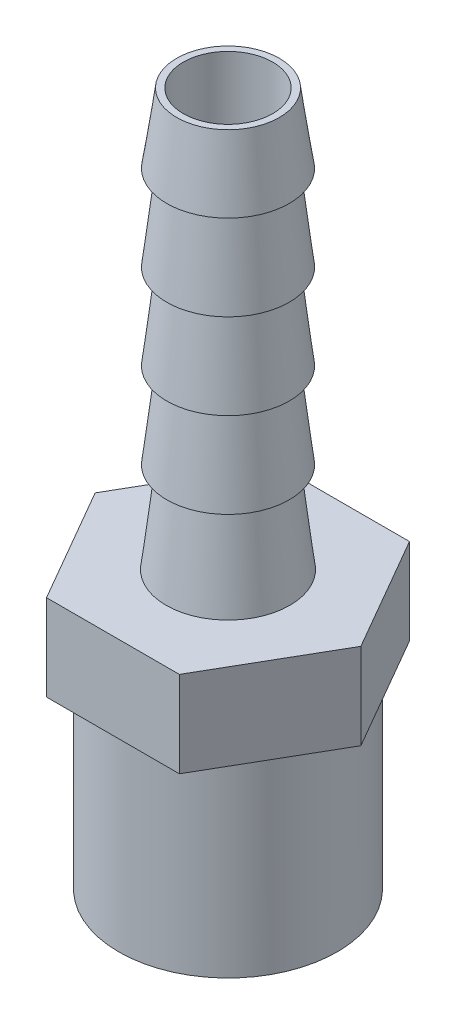
SolidWorks part; units mm, degrees
ref_plane "Front Plane" through (0, 0, 0) normal (0, 0, 1) x (1, 0, 0)
ref_plane "Top Plane" through (0, 0, 0) normal (0, 1, 0) x (1, 0, 0)
ref_plane "Right Plane" through (0, 0, 0) normal (1, 0, 0) x (0, 0, -1)
sketch "Sketch1" plane through (0, 0, 0) normal (0, 1, 0) x (1, 0, 0)
  line L1 (8.0252, 0) -> (4.0126, 6.95)
  line L2 (4.0126, 6.95) -> (-4.0126, 6.95)
  line L3 (-4.0126, 6.95) -> (-8.0252, 0)
  line L4 (-8.0252, 0) -> (-4.0126, -6.95)
  line L5 (-4.0126, -6.95) -> (4.0126, -6.95)
  line L6 (4.0126, -6.95) -> (8.0252, 0)
  circle A0 centre (0, 0) radius 6.95 construction
  circle A1 centre (0, 0) radius 2.7
  dimension "D2" = 5.4
  dimension "Hex Diameter" = 13.9
extrude "Boss-Extrude1" add sketch "Sketch1" against normal blind 5.2
sketch "Sketch2" plane through (0, 0, 0) normal (0, 0, 1) x (1, 0, 0)
  line L0 (2.7, 0) -> (2.7, 25.2)
  line L1 (-4.0126, 0) -> (4.0126, 0) construction
  line L2 (2.7, 25.2) -> (3.1, 25.2)
  line L3 (3.1, 25.2) -> (3.7, 21)
  line L4 (3.7, 21) -> (3.1, 21)
  line L5 (3.1, 21) -> (3.7, 15.8333)
  line L6 (3.7, 15.8333) -> (3.1, 15.8333)
  line L7 (3.1, 15.8333) -> (3.7, 10.6667)
  line L8 (3.7, 10.6667) -> (3.1, 10.6667)
  line L9 (3.1, 10.6667) -> (3.7, 5.5)
  line L10 (3.7, 5.5) -> (3.1, 5.5)
  line L11 (3.1, 5.5) -> (3.7387, 0)
  line L12 (3.7387, 0) -> (2.7, 0)
  line L13 (0, -1.9953) -> (0, 5.0004) construction
  point P15 (3.7, 16.8)
  dimension "D1" = 5.4
  dimension "D2" = 7.4
  dimension "D3" = 6.2
  dimension "D4" = 4.2
  dimension "D5" = 25.2
  dimension "D6" = 5.5
revolve "Revolve1" add sketch "Sketch2" angle 360 about L13
sketch "Lower Threads" plane through (0, -5.2, 0) normal (0, -1, 0) x (1, 0, 0)
  circle A0 centre (0, 0) radius 6.6
  circle A1 centre (0, 0) radius 4.5
  dimension "ID" = 9
  dimension "OD" = 13.2
extrude "Boss-Extrude2" add sketch "Lower Threads" along normal offset from surface (11.5 mm away) 16.7 up to face at (0, 0, 3.7387)
